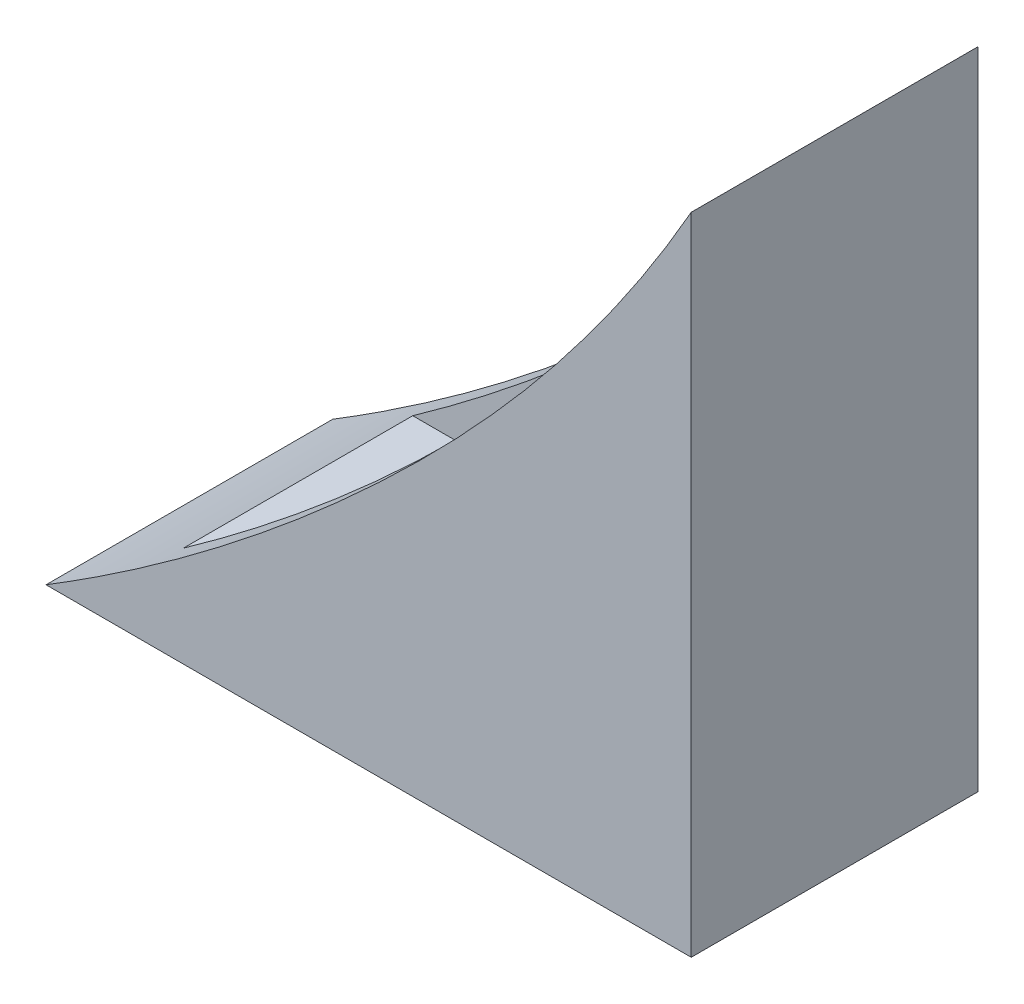
SolidWorks part; units mm, degrees
ref_plane "Front Plane" through (0, 0, 0) normal (0, 0, 1) x (1, 0, 0)
ref_plane "Top Plane" through (0, 0, 0) normal (0, 1, 0) x (1, 0, 0)
ref_plane "Right Plane" through (0, 0, 0) normal (1, 0, 0) x (0, 0, -1)
sketch "Sketch1" plane through (0, 0, 0) normal (0, 0, 1) x (1, 0, 0)
  line L0 (0, 0) -> (0, 45)
  line L2 (-45, 0) -> (0, 0)
  spline S0 degree 3 poles (0, 45) (-6.0431, 34.377) (-19.5966, 18.2905) (-36.769, 5.0476) (-45, 0) knots 0 0 0 0 0.55 1 1 1 1
  dimension "D1" = 45
  dimension "D2" = 45
extrude "Boss-Extrude1" add sketch "Sketch1" along normal blind 20
sketch "Sketch2" plane through (0, 0, 0) normal (0, -1, 0) x (1, 0, 0)
  line L0 (0, 20) -> (0, 0) construction
  line L1 (-45, 2) -> (-5, 2)
  line L2 (-45, 2) -> (-45, 18)
  line L3 (-45, 18) -> (-5, 18)
  line L4 (-5, 2) -> (-5, 18)
  line L5 (-45, 20) -> (-45, 0) construction
  line L6 (-45, 0) -> (0, 0) construction
  line L7 (0, 20) -> (-45, 20) construction
  dimension "D1" = 5
  dimension "D2" = 0
  dimension "D3" = 2
  dimension "D4" = 2
extrude "Cut-Extrude1" cut sketch "Sketch2" against normal through all from offset 5 offset against normal yes
